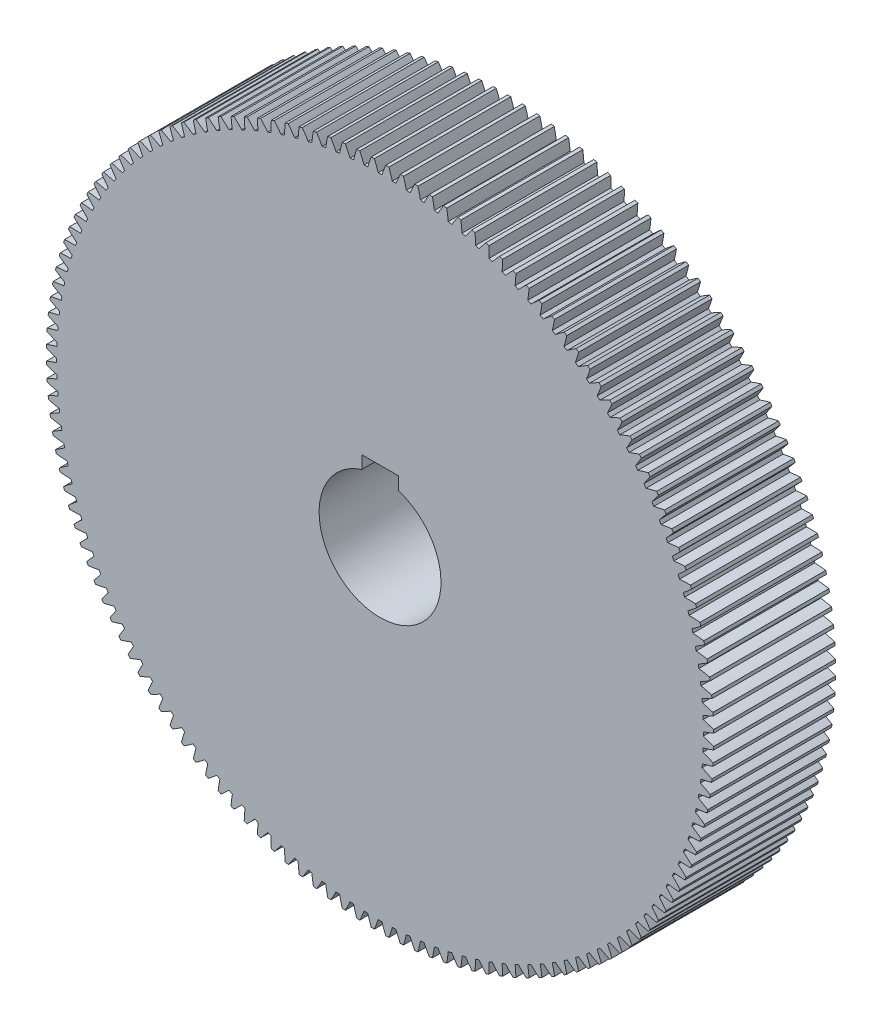
SolidWorks part; units mm, degrees
ref_plane "前视基准面" through (0, 0, 0) normal (0, 0, 1) x (1, 0, 0)
ref_plane "上视基准面" through (0, 0, 0) normal (0, 1, 0) x (1, 0, 0)
ref_plane "右视基准面" through (0, 0, 0) normal (1, 0, 0) x (0, 0, -1)
sketch "Model" plane through (0, 0, 0) normal (0, 0, 1) x (1, 0, 0)
  line L0 (6, 19.0788) -> (6, 23.3)
  line L1 (-6, 23.3) -> (-6, 19.0788)
  line L2 (6, 23.3) -> (-6, 23.3)
  arc A0 (-109.484, 1.8733) -> (-106.1223, 0.6043) centre (-92.5599, 41.6202) ccw
  arc A1 (-106.1223, 0.6043) -> (-106.1223, -0.6043) centre (0, 0) ccw
  arc A2 (-106.1223, -0.6043) -> (-109.484, -1.8733) centre (-92.5599, -41.6202) ccw
  arc A3 (-109.484, -1.8733) -> (-109.4615, -2.9041) centre (0, 0) ccw
  arc A4 (-109.4615, -2.9041) -> (-106.0476, -4.0252) centre (-94.2872, 37.5432) ccw
  arc A5 (-106.0476, -4.0252) -> (-105.9949, -5.2328) centre (0, 0) ccw
  arc A6 (-105.9949, -5.2328) -> (-109.2981, -6.6472) centre (-90.6563, -45.618) ccw
  arc A7 (-109.2981, -6.6472) -> (-109.2306, -7.676) centre (0, 0) ccw
  arc A8 (-109.2306, -7.676) -> (-105.7711, -8.6471) centre (-95.8351, 33.3947) ccw
  arc A9 (-105.7711, -8.6471) -> (-105.6658, -9.8512) centre (0, 0) ccw
  arc A10 (-105.6658, -9.8512) -> (-108.9041, -11.4084) centre (-88.5802, -49.529) ccw
  arc A11 (-108.9041, -11.4084) -> (-108.7918, -12.4332) centre (0, 0) ccw
  arc A12 (-108.7918, -12.4332) -> (-105.2933, -13.2526) centre (-97.2005, 29.1827) ccw
  arc A13 (-105.2933, -13.2526) -> (-105.1355, -14.4509) centre (0, 0) ccw
  arc A14 (-105.1355, -14.4509) -> (-108.3028, -16.1478) centre (-86.3355, -53.3456) ccw
  arc A15 (-108.3028, -16.1478) -> (-108.146, -17.1668) centre (0, 0) ccw
  arc A16 (-108.146, -17.1668) -> (-104.615, -17.8328) centre (-98.3809, 24.9151) ccw
  arc A17 (-104.615, -17.8328) -> (-104.4051, -19.0231) centre (0, 0) ccw
  arc A18 (-104.4051, -19.0231) -> (-107.4954, -20.8566) centre (-83.9264, -57.0608) ccw
  arc A19 (-107.4954, -20.8566) -> (-107.2942, -21.8677) centre (0, 0) ccw
  arc A20 (-107.2942, -21.8677) -> (-103.7376, -22.379) centre (-99.3741, 20.6) ccw
  arc A21 (-103.7376, -22.379) -> (-103.476, -23.5591) centre (0, 0) ccw
  arc A22 (-103.476, -23.5591) -> (-106.4833, -25.5256) centre (-81.3576, -60.6673) ccw
  arc A23 (-106.4833, -25.5256) -> (-106.2383, -26.527) centre (0, 0) ccw
  arc A24 (-106.2383, -26.527) -> (-102.6627, -26.8827) centre (-100.1781, 16.2458) ccw
  arc A25 (-102.6627, -26.8827) -> (-102.3498, -28.0502) centre (0, 0) ccw
  arc A26 (-102.3498, -28.0502) -> (-105.2685, -30.146) centre (-78.6339, -64.1583) ccw
  arc A27 (-105.2685, -30.146) -> (-104.98, -31.1358) centre (0, 0) ccw
  arc A28 (-104.98, -31.1358) -> (-101.3923, -31.3352) centre (-100.7914, 11.8606) ccw
  arc A29 (-101.3923, -31.3352) -> (-101.0289, -32.488) centre (0, 0) ccw
  arc A30 (-101.0289, -32.488) -> (-103.8534, -34.7091) centre (-75.7605, -67.5272) ccw
  arc A31 (-103.8534, -34.7091) -> (-103.522, -35.6854) centre (0, 0) ccw
  arc A32 (-103.522, -35.6854) -> (-99.929, -35.7281) centre (-101.2128, 7.4529) ccw
  arc A33 (-99.929, -35.7281) -> (-99.5156, -36.8639) centre (0, 0) ccw
  arc A34 (-99.5156, -36.8639) -> (-102.2406, -39.2061) centre (-72.7429, -70.7675) ccw
  arc A35 (-102.2406, -39.2061) -> (-101.8669, -40.167) centre (0, 0) ccw
  arc A36 (-101.8669, -40.167) -> (-98.2755, -40.0529) centre (-101.4415, 3.0309) ccw
  arc A37 (-98.2755, -40.0529) -> (-97.8129, -41.1696) centre (0, 0) ccw
  arc A38 (-97.8129, -41.1696) -> (-100.4331, -43.6284) centre (-69.5868, -73.8732) ccw
  arc A39 (-100.4331, -43.6284) -> (-100.0179, -44.5721) centre (0, 0) ccw
  arc A40 (-100.0179, -44.5721) -> (-96.4349, -44.3015) centre (-101.4772, -1.3968) ccw
  arc A41 (-96.4349, -44.3015) -> (-95.924, -45.3969) centre (0, 0) ccw
  arc A42 (-95.924, -45.3969) -> (-98.4345, -47.9677) centre (-66.2983, -76.8382) ccw
  arc A43 (-98.4345, -47.9677) -> (-97.9785, -48.8924) centre (0, 0) ccw
  arc A44 (-97.9785, -48.8924) -> (-94.4107, -48.4658) centre (-101.3197, -5.8218) ccw
  arc A45 (-94.4107, -48.4658) -> (-93.8526, -49.5379) centre (0, 0) ccw
  arc A46 (-93.8526, -49.5379) -> (-96.2485, -52.2157) centre (-62.8835, -79.657) ccw
  arc A47 (-96.2485, -52.2157) -> (-95.7526, -53.1196) centre (0, 0) ccw
  arc A48 (-95.7526, -53.1196) -> (-92.2068, -52.5378) centre (-100.9693, -10.2358) ccw
  arc A49 (-92.2068, -52.5378) -> (-91.6024, -53.5845) centre (0, 0) ccw
  arc A50 (-91.6024, -53.5845) -> (-93.8792, -56.3643) centre (-59.3491, -82.3241) ccw
  arc A51 (-93.8792, -56.3643) -> (-93.3444, -57.2457) centre (0, 0) ccw
  arc A52 (-93.3444, -57.2457) -> (-89.8273, -56.5098) centre (-100.4267, -14.6303) ccw
  arc A53 (-89.8273, -56.5098) -> (-89.1779, -57.5292) centre (0, 0) ccw
  arc A54 (-89.1779, -57.5292) -> (-91.3313, -60.4056) centre (-55.7017, -84.8345) ccw
  arc A55 (-91.3313, -60.4056) -> (-90.7585, -61.2629) centre (0, 0) ccw
  arc A56 (-90.7585, -61.2629) -> (-87.2769, -60.3742) centre (-99.693, -18.9969) ccw
  arc A57 (-87.2769, -60.3742) -> (-86.5836, -61.3643) centre (0, 0) ccw
  arc A58 (-86.5836, -61.3643) -> (-88.6095, -64.332) centre (-51.9482, -87.1834) ccw
  arc A59 (-88.6095, -64.332) -> (-87.9999, -65.1634) centre (0, 0) ccw
  arc A60 (-87.9999, -65.1634) -> (-84.5604, -64.1237) centre (-98.7695, -23.3273) ccw
  arc A61 (-84.5604, -64.1237) -> (-83.8246, -65.0826) centre (0, 0) ccw
  arc A62 (-83.8246, -65.0826) -> (-85.7191, -68.1358) centre (-48.0959, -89.3664) ccw
  arc A63 (-85.7191, -68.1358) -> (-85.0737, -68.9399) centre (0, 0) ccw
  arc A64 (-85.0737, -68.9399) -> (-81.6829, -67.7511) centre (-97.6579, -27.6134) ccw
  arc A65 (-81.6829, -67.7511) -> (-80.9059, -68.677) centre (0, 0) ccw
  arc A66 (-80.9059, -68.677) -> (-82.6654, -71.81) centre (-44.152, -91.3793) ccw
  arc A67 (-82.6654, -71.81) -> (-81.9857, -72.5851) centre (0, 0) ccw
  arc A68 (-81.9857, -72.5851) -> (-78.6498, -71.2496) centre (-96.3605, -31.8469) ccw
  arc A69 (-78.6498, -71.2496) -> (-77.8333, -72.1407) centre (0, 0) ccw
  arc A70 (-77.8333, -72.1407) -> (-79.4544, -75.3475) centre (-40.1241, -93.2182) ccw
  arc A71 (-79.4544, -75.3475) -> (-78.7415, -76.0922) centre (0, 0) ccw
  arc A72 (-78.7415, -76.0922) -> (-75.4671, -74.6124) centre (-94.8796, -36.0198) ccw
  arc A73 (-75.4671, -74.6124) -> (-74.6124, -75.4671) centre (0, 0) ccw
  arc A74 (-74.6124, -75.4671) -> (-76.0922, -78.7415) centre (-36.0198, -94.8796) ccw
  arc A75 (-76.0922, -78.7415) -> (-75.3475, -79.4544) centre (0, 0) ccw
  arc A76 (-75.3475, -79.4544) -> (-72.1407, -77.8333) centre (-93.2182, -40.1241) ccw
  arc A77 (-72.1407, -77.8333) -> (-71.2496, -78.6498) centre (0, 0) ccw
  arc A78 (-71.2496, -78.6498) -> (-72.5851, -81.9857) centre (-31.8469, -96.3605) ccw
  arc A79 (-72.5851, -81.9857) -> (-71.81, -82.6654) centre (0, 0) ccw
  arc A80 (-71.81, -82.6654) -> (-68.677, -80.9059) centre (-91.3793, -44.152) ccw
  arc A81 (-68.677, -80.9059) -> (-67.7511, -81.6829) centre (0, 0) ccw
  arc A82 (-67.7511, -81.6829) -> (-68.9399, -85.0737) centre (-27.6134, -97.6579) ccw
  arc A83 (-68.9399, -85.0737) -> (-68.1358, -85.7191) centre (0, 0) ccw
  arc A84 (-68.1358, -85.7191) -> (-65.0826, -83.8246) centre (-89.3664, -48.0959) ccw
  arc A85 (-65.0826, -83.8246) -> (-64.1237, -84.5604) centre (0, 0) ccw
  arc A86 (-64.1237, -84.5604) -> (-65.1634, -87.9999) centre (-23.3273, -98.7695) ccw
  arc A87 (-65.1634, -87.9999) -> (-64.332, -88.6095) centre (0, 0) ccw
  arc A88 (-64.332, -88.6095) -> (-61.3643, -86.5836) centre (-87.1834, -51.9482) ccw
  arc A89 (-61.3643, -86.5836) -> (-60.3742, -87.2769) centre (0, 0) ccw
  arc A90 (-60.3742, -87.2769) -> (-61.2629, -90.7585) centre (-18.9969, -99.693) ccw
  arc A91 (-61.2629, -90.7585) -> (-60.4056, -91.3313) centre (0, 0) ccw
  arc A92 (-60.4056, -91.3313) -> (-57.5292, -89.1779) centre (-84.8345, -55.7017) ccw
  arc A93 (-57.5292, -89.1779) -> (-56.5098, -89.8273) centre (0, 0) ccw
  arc A94 (-56.5098, -89.8273) -> (-57.2457, -93.3444) centre (-14.6303, -100.4267) ccw
  arc A95 (-57.2457, -93.3444) -> (-56.3643, -93.8792) centre (0, 0) ccw
  arc A96 (-56.3643, -93.8792) -> (-53.5845, -91.6024) centre (-82.3241, -59.3491) ccw
  arc A97 (-53.5845, -91.6024) -> (-52.5378, -92.2068) centre (0, 0) ccw
  arc A98 (-52.5378, -92.2068) -> (-53.1196, -95.7526) centre (-10.2358, -100.9693) ccw
  arc A99 (-53.1196, -95.7526) -> (-52.2157, -96.2485) centre (0, 0) ccw
  arc A100 (-52.2157, -96.2485) -> (-49.5379, -93.8526) centre (-79.657, -62.8835) ccw
  arc A101 (-49.5379, -93.8526) -> (-48.4658, -94.4107) centre (0, 0) ccw
  arc A102 (-48.4658, -94.4107) -> (-48.8924, -97.9785) centre (-5.8218, -101.3197) ccw
  arc A103 (-48.8924, -97.9785) -> (-47.9677, -98.4345) centre (0, 0) ccw
  arc A104 (-47.9677, -98.4345) -> (-45.3969, -95.924) centre (-76.8382, -66.2983) ccw
  arc A105 (-45.3969, -95.924) -> (-44.3015, -96.4349) centre (0, 0) ccw
  arc A106 (-44.3015, -96.4349) -> (-44.5721, -100.0179) centre (-1.3968, -101.4772) ccw
  arc A107 (-44.5721, -100.0179) -> (-43.6284, -100.4331) centre (0, 0) ccw
  arc A108 (-43.6284, -100.4331) -> (-41.1696, -97.8129) centre (-73.8732, -69.5868) ccw
  arc A109 (-41.1696, -97.8129) -> (-40.0529, -98.2755) centre (0, 0) ccw
  arc A110 (-40.0529, -98.2755) -> (-40.167, -101.8669) centre (3.0309, -101.4415) ccw
  arc A111 (-40.167, -101.8669) -> (-39.2061, -102.2406) centre (0, 0) ccw
  arc A112 (-39.2061, -102.2406) -> (-36.8639, -99.5156) centre (-70.7675, -72.7429) ccw
  arc A113 (-36.8639, -99.5156) -> (-35.7281, -99.929) centre (0, 0) ccw
  arc A114 (-35.7281, -99.929) -> (-35.6854, -103.522) centre (7.4529, -101.2128) ccw
  arc A115 (-35.6854, -103.522) -> (-34.7091, -103.8534) centre (0, 0) ccw
  arc A116 (-34.7091, -103.8534) -> (-32.488, -101.0289) centre (-67.5272, -75.7605) ccw
  arc A117 (-32.488, -101.0289) -> (-31.3352, -101.3923) centre (0, 0) ccw
  arc A118 (-31.3352, -101.3923) -> (-31.1358, -104.98) centre (11.8606, -100.7914) ccw
  arc A119 (-31.1358, -104.98) -> (-30.146, -105.2685) centre (0, 0) ccw
  arc A120 (-30.146, -105.2685) -> (-28.0502, -102.3498) centre (-64.1583, -78.6339) ccw
  arc A121 (-28.0502, -102.3498) -> (-26.8827, -102.6627) centre (0, 0) ccw
  arc A122 (-26.8827, -102.6627) -> (-26.527, -106.2383) centre (16.2458, -100.1781) ccw
  arc A123 (-26.527, -106.2383) -> (-25.5256, -106.4833) centre (0, 0) ccw
  arc A124 (-25.5256, -106.4833) -> (-23.5591, -103.476) centre (-60.6673, -81.3576) ccw
  arc A125 (-23.5591, -103.476) -> (-22.379, -103.7376) centre (0, 0) ccw
  arc A126 (-22.379, -103.7376) -> (-21.8677, -107.2942) centre (20.6, -99.3741) ccw
  arc A127 (-21.8677, -107.2942) -> (-20.8566, -107.4954) centre (0, 0) ccw
  arc A128 (-20.8566, -107.4954) -> (-19.0231, -104.4051) centre (-57.0608, -83.9264) ccw
  arc A129 (-19.0231, -104.4051) -> (-17.8328, -104.615) centre (0, 0) ccw
  arc A130 (-17.8328, -104.615) -> (-17.1668, -108.146) centre (24.9151, -98.3809) ccw
  arc A131 (-17.1668, -108.146) -> (-16.1478, -108.3028) centre (0, 0) ccw
  arc A132 (-16.1478, -108.3028) -> (-14.4509, -105.1355) centre (-53.3456, -86.3355) ccw
  arc A133 (-14.4509, -105.1355) -> (-13.2526, -105.2933) centre (0, 0) ccw
  arc A134 (-13.2526, -105.2933) -> (-12.4332, -108.7918) centre (29.1827, -97.2005) ccw
  arc A135 (-12.4332, -108.7918) -> (-11.4084, -108.9041) centre (0, 0) ccw
  arc A136 (-11.4084, -108.9041) -> (-9.8512, -105.6658) centre (-49.529, -88.5802) ccw
  arc A137 (-9.8512, -105.6658) -> (-8.6471, -105.7711) centre (0, 0) ccw
  arc A138 (-8.6471, -105.7711) -> (-7.676, -109.2306) centre (33.3947, -95.8351) ccw
  arc A139 (-7.676, -109.2306) -> (-6.6472, -109.2981) centre (0, 0) ccw
  arc A140 (-6.6472, -109.2981) -> (-5.2328, -105.9949) centre (-45.618, -90.6563) ccw
  arc A141 (-5.2328, -105.9949) -> (-4.0252, -106.0476) centre (0, 0) ccw
  arc A142 (-4.0252, -106.0476) -> (-2.9041, -109.4615) centre (37.5432, -94.2872) ccw
  arc A143 (-2.9041, -109.4615) -> (-1.8733, -109.484) centre (0, 0) ccw
  arc A144 (-1.8733, -109.484) -> (-0.6043, -106.1223) centre (-41.6202, -92.5599) ccw
  arc A145 (-0.6043, -106.1223) -> (0.6043, -106.1223) centre (0, 0) ccw
  arc A146 (0.6043, -106.1223) -> (1.8733, -109.484) centre (41.6202, -92.5599) ccw
  arc A147 (1.8733, -109.484) -> (2.9041, -109.4615) centre (0, 0) ccw
  arc A148 (2.9041, -109.4615) -> (4.0252, -106.0476) centre (-37.5432, -94.2872) ccw
  arc A149 (4.0252, -106.0476) -> (5.2328, -105.9949) centre (0, 0) ccw
  arc A150 (5.2328, -105.9949) -> (6.6472, -109.2981) centre (45.618, -90.6563) ccw
  arc A151 (6.6472, -109.2981) -> (7.676, -109.2306) centre (0, 0) ccw
  arc A152 (7.676, -109.2306) -> (8.6471, -105.7711) centre (-33.3947, -95.8351) ccw
  arc A153 (8.6471, -105.7711) -> (9.8512, -105.6658) centre (0, 0) ccw
  arc A154 (9.8512, -105.6658) -> (11.4084, -108.9041) centre (49.529, -88.5802) ccw
  arc A155 (11.4084, -108.9041) -> (12.4332, -108.7918) centre (0, 0) ccw
  arc A156 (12.4332, -108.7918) -> (13.2526, -105.2933) centre (-29.1827, -97.2005) ccw
  arc A157 (13.2526, -105.2933) -> (14.4509, -105.1355) centre (0, 0) ccw
  arc A158 (14.4509, -105.1355) -> (16.1478, -108.3028) centre (53.3456, -86.3355) ccw
  arc A159 (16.1478, -108.3028) -> (17.1668, -108.146) centre (0, 0) ccw
  arc A160 (17.1668, -108.146) -> (17.8328, -104.615) centre (-24.9151, -98.3809) ccw
  arc A161 (17.8328, -104.615) -> (19.0231, -104.4051) centre (0, 0) ccw
  arc A162 (19.0231, -104.4051) -> (20.8566, -107.4954) centre (57.0608, -83.9264) ccw
  arc A163 (20.8566, -107.4954) -> (21.8677, -107.2942) centre (0, 0) ccw
  arc A164 (21.8677, -107.2942) -> (22.379, -103.7376) centre (-20.6, -99.3741) ccw
  arc A165 (22.379, -103.7376) -> (23.5591, -103.476) centre (0, 0) ccw
  arc A166 (23.5591, -103.476) -> (25.5256, -106.4833) centre (60.6673, -81.3576) ccw
  arc A167 (25.5256, -106.4833) -> (26.527, -106.2383) centre (0, 0) ccw
  arc A168 (26.527, -106.2383) -> (26.8827, -102.6627) centre (-16.2458, -100.1781) ccw
  arc A169 (26.8827, -102.6627) -> (28.0502, -102.3498) centre (0, 0) ccw
  arc A170 (28.0502, -102.3498) -> (30.146, -105.2685) centre (64.1583, -78.6339) ccw
  arc A171 (30.146, -105.2685) -> (31.1358, -104.98) centre (0, 0) ccw
  arc A172 (31.1358, -104.98) -> (31.3352, -101.3923) centre (-11.8606, -100.7914) ccw
  arc A173 (31.3352, -101.3923) -> (32.488, -101.0289) centre (0, 0) ccw
  arc A174 (32.488, -101.0289) -> (34.7091, -103.8534) centre (67.5272, -75.7605) ccw
  arc A175 (34.7091, -103.8534) -> (35.6854, -103.522) centre (0, 0) ccw
  arc A176 (35.6854, -103.522) -> (35.7281, -99.929) centre (-7.4529, -101.2128) ccw
  arc A177 (35.7281, -99.929) -> (36.8639, -99.5156) centre (0, 0) ccw
  arc A178 (36.8639, -99.5156) -> (39.2061, -102.2406) centre (70.7675, -72.7429) ccw
  arc A179 (39.2061, -102.2406) -> (40.167, -101.8669) centre (0, 0) ccw
  arc A180 (40.167, -101.8669) -> (40.0529, -98.2755) centre (-3.0309, -101.4415) ccw
  arc A181 (40.0529, -98.2755) -> (41.1696, -97.8129) centre (0, 0) ccw
  arc A182 (41.1696, -97.8129) -> (43.6284, -100.4331) centre (73.8732, -69.5868) ccw
  arc A183 (43.6284, -100.4331) -> (44.5721, -100.0179) centre (0, 0) ccw
  arc A184 (44.5721, -100.0179) -> (44.3015, -96.4349) centre (1.3968, -101.4772) ccw
  arc A185 (44.3015, -96.4349) -> (45.3969, -95.924) centre (0, 0) ccw
  arc A186 (45.3969, -95.924) -> (47.9677, -98.4345) centre (76.8382, -66.2983) ccw
  arc A187 (47.9677, -98.4345) -> (48.8924, -97.9785) centre (0, 0) ccw
  arc A188 (48.8924, -97.9785) -> (48.4658, -94.4107) centre (5.8218, -101.3197) ccw
  arc A189 (48.4658, -94.4107) -> (49.5379, -93.8526) centre (0, 0) ccw
  arc A190 (49.5379, -93.8526) -> (52.2157, -96.2485) centre (79.657, -62.8835) ccw
  arc A191 (52.2157, -96.2485) -> (53.1196, -95.7526) centre (0, 0) ccw
  arc A192 (53.1196, -95.7526) -> (52.5378, -92.2068) centre (10.2358, -100.9693) ccw
  arc A193 (52.5378, -92.2068) -> (53.5845, -91.6024) centre (0, 0) ccw
  arc A194 (53.5845, -91.6024) -> (56.3643, -93.8792) centre (82.3241, -59.3491) ccw
  arc A195 (56.3643, -93.8792) -> (57.2457, -93.3444) centre (0, 0) ccw
  arc A196 (57.2457, -93.3444) -> (56.5098, -89.8273) centre (14.6303, -100.4267) ccw
  arc A197 (56.5098, -89.8273) -> (57.5292, -89.1779) centre (0, 0) ccw
  arc A198 (57.5292, -89.1779) -> (60.4056, -91.3313) centre (84.8345, -55.7017) ccw
  arc A199 (60.4056, -91.3313) -> (61.2629, -90.7585) centre (0, 0) ccw
  arc A200 (61.2629, -90.7585) -> (60.3742, -87.2769) centre (18.9969, -99.693) ccw
  arc A201 (60.3742, -87.2769) -> (61.3643, -86.5836) centre (0, 0) ccw
  arc A202 (61.3643, -86.5836) -> (64.332, -88.6095) centre (87.1834, -51.9482) ccw
  arc A203 (64.332, -88.6095) -> (65.1634, -87.9999) centre (0, 0) ccw
  arc A204 (65.1634, -87.9999) -> (64.1237, -84.5604) centre (23.3273, -98.7695) ccw
  arc A205 (64.1237, -84.5604) -> (65.0826, -83.8246) centre (0, 0) ccw
  arc A206 (65.0826, -83.8246) -> (68.1358, -85.7191) centre (89.3664, -48.0959) ccw
  arc A207 (68.1358, -85.7191) -> (68.9399, -85.0737) centre (0, 0) ccw
  arc A208 (68.9399, -85.0737) -> (67.7511, -81.6829) centre (27.6134, -97.6579) ccw
  arc A209 (67.7511, -81.6829) -> (68.677, -80.9059) centre (0, 0) ccw
  arc A210 (68.677, -80.9059) -> (71.81, -82.6654) centre (91.3793, -44.152) ccw
  arc A211 (71.81, -82.6654) -> (72.5851, -81.9857) centre (0, 0) ccw
  arc A212 (72.5851, -81.9857) -> (71.2496, -78.6498) centre (31.8469, -96.3605) ccw
  arc A213 (71.2496, -78.6498) -> (72.1407, -77.8333) centre (0, 0) ccw
  arc A214 (72.1407, -77.8333) -> (75.3475, -79.4544) centre (93.2182, -40.1241) ccw
  arc A215 (75.3475, -79.4544) -> (76.0922, -78.7415) centre (0, 0) ccw
  arc A216 (76.0922, -78.7415) -> (74.6124, -75.4671) centre (36.0198, -94.8796) ccw
  arc A217 (74.6124, -75.4671) -> (75.4671, -74.6124) centre (0, 0) ccw
  arc A218 (75.4671, -74.6124) -> (78.7415, -76.0922) centre (94.8796, -36.0198) ccw
  arc A219 (78.7415, -76.0922) -> (79.4544, -75.3475) centre (0, 0) ccw
  arc A220 (79.4544, -75.3475) -> (77.8333, -72.1407) centre (40.1241, -93.2182) ccw
  arc A221 (77.8333, -72.1407) -> (78.6498, -71.2496) centre (0, 0) ccw
  arc A222 (78.6498, -71.2496) -> (81.9857, -72.5851) centre (96.3605, -31.8469) ccw
  arc A223 (81.9857, -72.5851) -> (82.6654, -71.81) centre (0, 0) ccw
  arc A224 (82.6654, -71.81) -> (80.9059, -68.677) centre (44.152, -91.3793) ccw
  arc A225 (80.9059, -68.677) -> (81.6829, -67.7511) centre (0, 0) ccw
  arc A226 (81.6829, -67.7511) -> (85.0737, -68.9399) centre (97.6579, -27.6134) ccw
  arc A227 (85.0737, -68.9399) -> (85.7191, -68.1358) centre (0, 0) ccw
  arc A228 (85.7191, -68.1358) -> (83.8246, -65.0826) centre (48.0959, -89.3664) ccw
  arc A229 (83.8246, -65.0826) -> (84.5604, -64.1237) centre (0, 0) ccw
  arc A230 (84.5604, -64.1237) -> (87.9999, -65.1634) centre (98.7695, -23.3273) ccw
  arc A231 (87.9999, -65.1634) -> (88.6095, -64.332) centre (0, 0) ccw
  arc A232 (88.6095, -64.332) -> (86.5836, -61.3643) centre (51.9482, -87.1834) ccw
  arc A233 (86.5836, -61.3643) -> (87.2769, -60.3742) centre (0, 0) ccw
  arc A234 (87.2769, -60.3742) -> (90.7585, -61.2629) centre (99.693, -18.9969) ccw
  arc A235 (90.7585, -61.2629) -> (91.3313, -60.4056) centre (0, 0) ccw
  arc A236 (91.3313, -60.4056) -> (89.1779, -57.5292) centre (55.7017, -84.8345) ccw
  arc A237 (89.1779, -57.5292) -> (89.8273, -56.5098) centre (0, 0) ccw
  arc A238 (89.8273, -56.5098) -> (93.3444, -57.2457) centre (100.4267, -14.6303) ccw
  arc A239 (93.3444, -57.2457) -> (93.8792, -56.3643) centre (0, 0) ccw
  arc A240 (93.8792, -56.3643) -> (91.6024, -53.5845) centre (59.3491, -82.3241) ccw
  arc A241 (91.6024, -53.5845) -> (92.2068, -52.5378) centre (0, 0) ccw
  arc A242 (92.2068, -52.5378) -> (95.7526, -53.1196) centre (100.9693, -10.2358) ccw
  arc A243 (95.7526, -53.1196) -> (96.2485, -52.2157) centre (0, 0) ccw
  arc A244 (96.2485, -52.2157) -> (93.8526, -49.5379) centre (62.8835, -79.657) ccw
  arc A245 (93.8526, -49.5379) -> (94.4107, -48.4658) centre (0, 0) ccw
  arc A246 (94.4107, -48.4658) -> (97.9785, -48.8924) centre (101.3197, -5.8218) ccw
  arc A247 (97.9785, -48.8924) -> (98.4345, -47.9677) centre (0, 0) ccw
  arc A248 (98.4345, -47.9677) -> (95.924, -45.3969) centre (66.2983, -76.8382) ccw
  arc A249 (95.924, -45.3969) -> (96.4349, -44.3015) centre (0, 0) ccw
  arc A250 (96.4349, -44.3015) -> (100.0179, -44.5721) centre (101.4772, -1.3968) ccw
  arc A251 (100.0179, -44.5721) -> (100.4331, -43.6284) centre (0, 0) ccw
  arc A252 (100.4331, -43.6284) -> (97.8129, -41.1696) centre (69.5868, -73.8732) ccw
  arc A253 (97.8129, -41.1696) -> (98.2755, -40.0529) centre (0, 0) ccw
  arc A254 (98.2755, -40.0529) -> (101.8669, -40.167) centre (101.4415, 3.0309) ccw
  arc A255 (101.8669, -40.167) -> (102.2406, -39.2061) centre (0, 0) ccw
  arc A256 (102.2406, -39.2061) -> (99.5156, -36.8639) centre (72.7429, -70.7675) ccw
  arc A257 (99.5156, -36.8639) -> (99.929, -35.7281) centre (0, 0) ccw
  arc A258 (99.929, -35.7281) -> (103.522, -35.6854) centre (101.2128, 7.4529) ccw
  arc A259 (103.522, -35.6854) -> (103.8534, -34.7091) centre (0, 0) ccw
  arc A260 (103.8534, -34.7091) -> (101.0289, -32.488) centre (75.7605, -67.5272) ccw
  arc A261 (101.0289, -32.488) -> (101.3923, -31.3352) centre (0, 0) ccw
  arc A262 (101.3923, -31.3352) -> (104.98, -31.1358) centre (100.7914, 11.8606) ccw
  arc A263 (104.98, -31.1358) -> (105.2685, -30.146) centre (0, 0) ccw
  arc A264 (105.2685, -30.146) -> (102.3498, -28.0502) centre (78.6339, -64.1583) ccw
  arc A265 (102.3498, -28.0502) -> (102.6627, -26.8827) centre (0, 0) ccw
  arc A266 (102.6627, -26.8827) -> (106.2383, -26.527) centre (100.1781, 16.2458) ccw
  arc A267 (106.2383, -26.527) -> (106.4833, -25.5256) centre (0, 0) ccw
  arc A268 (106.4833, -25.5256) -> (103.476, -23.5591) centre (81.3576, -60.6673) ccw
  arc A269 (103.476, -23.5591) -> (103.7376, -22.379) centre (0, 0) ccw
  arc A270 (103.7376, -22.379) -> (107.2942, -21.8677) centre (99.3741, 20.6) ccw
  arc A271 (107.2942, -21.8677) -> (107.4954, -20.8566) centre (0, 0) ccw
  arc A272 (107.4954, -20.8566) -> (104.4051, -19.0231) centre (83.9264, -57.0608) ccw
  arc A273 (104.4051, -19.0231) -> (104.615, -17.8328) centre (0, 0) ccw
  arc A274 (104.615, -17.8328) -> (108.146, -17.1668) centre (98.3809, 24.9151) ccw
  arc A275 (108.146, -17.1668) -> (108.3028, -16.1478) centre (0, 0) ccw
  arc A276 (108.3028, -16.1478) -> (105.1355, -14.4509) centre (86.3355, -53.3456) ccw
  arc A277 (105.1355, -14.4509) -> (105.2933, -13.2526) centre (0, 0) ccw
  arc A278 (105.2933, -13.2526) -> (108.7918, -12.4332) centre (97.2005, 29.1827) ccw
  arc A279 (108.7918, -12.4332) -> (108.9041, -11.4084) centre (0, 0) ccw
  arc A280 (108.9041, -11.4084) -> (105.6658, -9.8512) centre (88.5802, -49.529) ccw
  arc A281 (105.6658, -9.8512) -> (105.7711, -8.6471) centre (0, 0) ccw
  arc A282 (105.7711, -8.6471) -> (109.2306, -7.676) centre (95.8351, 33.3947) ccw
  arc A283 (109.2306, -7.676) -> (109.2981, -6.6472) centre (0, 0) ccw
  arc A284 (109.2981, -6.6472) -> (105.9949, -5.2328) centre (90.6563, -45.618) ccw
  arc A285 (105.9949, -5.2328) -> (106.0476, -4.0252) centre (0, 0) ccw
  arc A286 (106.0476, -4.0252) -> (109.4615, -2.9041) centre (94.2872, 37.5432) ccw
  arc A287 (109.4615, -2.9041) -> (109.484, -1.8733) centre (0, 0) ccw
  arc A288 (109.484, -1.8733) -> (106.1223, -0.6043) centre (92.5599, -41.6202) ccw
  arc A289 (106.1223, -0.6043) -> (106.1223, 0.6043) centre (0, 0) ccw
  arc A290 (106.1223, 0.6043) -> (109.484, 1.8733) centre (92.5599, 41.6202) ccw
  arc A291 (109.484, 1.8733) -> (109.4615, 2.9041) centre (0, 0) ccw
  arc A292 (109.4615, 2.9041) -> (106.0476, 4.0252) centre (94.2872, -37.5432) ccw
  arc A293 (106.0476, 4.0252) -> (105.9949, 5.2328) centre (0, 0) ccw
  arc A294 (105.9949, 5.2328) -> (109.2981, 6.6472) centre (90.6563, 45.618) ccw
  arc A295 (109.2981, 6.6472) -> (109.2306, 7.676) centre (0, 0) ccw
  arc A296 (109.2306, 7.676) -> (105.7711, 8.6471) centre (95.8351, -33.3947) ccw
  arc A297 (105.7711, 8.6471) -> (105.6658, 9.8512) centre (0, 0) ccw
  arc A298 (105.6658, 9.8512) -> (108.9041, 11.4084) centre (88.5802, 49.529) ccw
  arc A299 (108.9041, 11.4084) -> (108.7918, 12.4332) centre (0, 0) ccw
  arc A300 (108.7918, 12.4332) -> (105.2933, 13.2526) centre (97.2005, -29.1827) ccw
  arc A301 (105.2933, 13.2526) -> (105.1355, 14.4509) centre (0, 0) ccw
  arc A302 (105.1355, 14.4509) -> (108.3028, 16.1478) centre (86.3355, 53.3456) ccw
  arc A303 (108.3028, 16.1478) -> (108.146, 17.1668) centre (0, 0) ccw
  arc A304 (108.146, 17.1668) -> (104.615, 17.8328) centre (98.3809, -24.9151) ccw
  arc A305 (104.615, 17.8328) -> (104.4051, 19.0231) centre (0, 0) ccw
  arc A306 (104.4051, 19.0231) -> (107.4954, 20.8566) centre (83.9264, 57.0608) ccw
  arc A307 (107.4954, 20.8566) -> (107.2942, 21.8677) centre (0, 0) ccw
  arc A308 (107.2942, 21.8677) -> (103.7376, 22.379) centre (99.3741, -20.6) ccw
  arc A309 (103.7376, 22.379) -> (103.476, 23.5591) centre (0, 0) ccw
  arc A310 (103.476, 23.5591) -> (106.4833, 25.5256) centre (81.3576, 60.6673) ccw
  arc A311 (106.4833, 25.5256) -> (106.2383, 26.527) centre (0, 0) ccw
  arc A312 (106.2383, 26.527) -> (102.6627, 26.8827) centre (100.1781, -16.2458) ccw
  arc A313 (102.6627, 26.8827) -> (102.3498, 28.0502) centre (0, 0) ccw
  arc A314 (102.3498, 28.0502) -> (105.2685, 30.146) centre (78.6339, 64.1583) ccw
  arc A315 (105.2685, 30.146) -> (104.98, 31.1358) centre (0, 0) ccw
  arc A316 (104.98, 31.1358) -> (101.3923, 31.3352) centre (100.7914, -11.8606) ccw
  arc A317 (101.3923, 31.3352) -> (101.0289, 32.488) centre (0, 0) ccw
  arc A318 (101.0289, 32.488) -> (103.8534, 34.7091) centre (75.7605, 67.5272) ccw
  arc A319 (103.8534, 34.7091) -> (103.522, 35.6854) centre (0, 0) ccw
  arc A320 (103.522, 35.6854) -> (99.929, 35.7281) centre (101.2128, -7.4529) ccw
  arc A321 (99.929, 35.7281) -> (99.5156, 36.8639) centre (0, 0) ccw
  arc A322 (99.5156, 36.8639) -> (102.2406, 39.2061) centre (72.7429, 70.7675) ccw
  arc A323 (102.2406, 39.2061) -> (101.8669, 40.167) centre (0, 0) ccw
  arc A324 (101.8669, 40.167) -> (98.2755, 40.0529) centre (101.4415, -3.0309) ccw
  arc A325 (98.2755, 40.0529) -> (97.8129, 41.1696) centre (0, 0) ccw
  arc A326 (97.8129, 41.1696) -> (100.4331, 43.6284) centre (69.5868, 73.8732) ccw
  arc A327 (100.4331, 43.6284) -> (100.0179, 44.5721) centre (0, 0) ccw
  arc A328 (100.0179, 44.5721) -> (96.4349, 44.3015) centre (101.4772, 1.3968) ccw
  arc A329 (96.4349, 44.3015) -> (95.924, 45.3969) centre (0, 0) ccw
  arc A330 (95.924, 45.3969) -> (98.4345, 47.9677) centre (66.2983, 76.8382) ccw
  arc A331 (98.4345, 47.9677) -> (97.9785, 48.8924) centre (0, 0) ccw
  arc A332 (97.9785, 48.8924) -> (94.4107, 48.4658) centre (101.3197, 5.8218) ccw
  arc A333 (94.4107, 48.4658) -> (93.8526, 49.5379) centre (0, 0) ccw
  arc A334 (93.8526, 49.5379) -> (96.2485, 52.2157) centre (62.8835, 79.657) ccw
  arc A335 (96.2485, 52.2157) -> (95.7526, 53.1196) centre (0, 0) ccw
  arc A336 (95.7526, 53.1196) -> (92.2068, 52.5378) centre (100.9693, 10.2358) ccw
  arc A337 (92.2068, 52.5378) -> (91.6024, 53.5845) centre (0, 0) ccw
  arc A338 (91.6024, 53.5845) -> (93.8792, 56.3643) centre (59.3491, 82.3241) ccw
  arc A339 (93.8792, 56.3643) -> (93.3444, 57.2457) centre (0, 0) ccw
  arc A340 (93.3444, 57.2457) -> (89.8273, 56.5098) centre (100.4267, 14.6303) ccw
  arc A341 (89.8273, 56.5098) -> (89.1779, 57.5292) centre (0, 0) ccw
  arc A342 (89.1779, 57.5292) -> (91.3313, 60.4056) centre (55.7017, 84.8345) ccw
  arc A343 (91.3313, 60.4056) -> (90.7585, 61.2629) centre (0, 0) ccw
  arc A344 (90.7585, 61.2629) -> (87.2769, 60.3742) centre (99.693, 18.9969) ccw
  arc A345 (87.2769, 60.3742) -> (86.5836, 61.3643) centre (0, 0) ccw
  arc A346 (86.5836, 61.3643) -> (88.6095, 64.332) centre (51.9482, 87.1834) ccw
  arc A347 (88.6095, 64.332) -> (87.9999, 65.1634) centre (0, 0) ccw
  arc A348 (87.9999, 65.1634) -> (84.5604, 64.1237) centre (98.7695, 23.3273) ccw
  arc A349 (84.5604, 64.1237) -> (83.8246, 65.0826) centre (0, 0) ccw
  arc A350 (83.8246, 65.0826) -> (85.7191, 68.1358) centre (48.0959, 89.3664) ccw
  arc A351 (85.7191, 68.1358) -> (85.0737, 68.9399) centre (0, 0) ccw
  arc A352 (85.0737, 68.9399) -> (81.6829, 67.7511) centre (97.6579, 27.6134) ccw
  arc A353 (81.6829, 67.7511) -> (80.9059, 68.677) centre (0, 0) ccw
  arc A354 (80.9059, 68.677) -> (82.6654, 71.81) centre (44.152, 91.3793) ccw
  arc A355 (82.6654, 71.81) -> (81.9857, 72.5851) centre (0, 0) ccw
  arc A356 (81.9857, 72.5851) -> (78.6498, 71.2496) centre (96.3605, 31.8469) ccw
  arc A357 (78.6498, 71.2496) -> (77.8333, 72.1407) centre (0, 0) ccw
  arc A358 (77.8333, 72.1407) -> (79.4544, 75.3475) centre (40.1241, 93.2182) ccw
  arc A359 (79.4544, 75.3475) -> (78.7415, 76.0922) centre (0, 0) ccw
  arc A360 (78.7415, 76.0922) -> (75.4671, 74.6124) centre (94.8796, 36.0198) ccw
  arc A361 (75.4671, 74.6124) -> (74.6124, 75.4671) centre (0, 0) ccw
  arc A362 (74.6124, 75.4671) -> (76.0922, 78.7415) centre (36.0198, 94.8796) ccw
  arc A363 (76.0922, 78.7415) -> (75.3475, 79.4544) centre (0, 0) ccw
  arc A364 (75.3475, 79.4544) -> (72.1407, 77.8333) centre (93.2182, 40.1241) ccw
  arc A365 (72.1407, 77.8333) -> (71.2496, 78.6498) centre (0, 0) ccw
  arc A366 (71.2496, 78.6498) -> (72.5851, 81.9857) centre (31.8469, 96.3605) ccw
  arc A367 (72.5851, 81.9857) -> (71.81, 82.6654) centre (0, 0) ccw
  arc A368 (71.81, 82.6654) -> (68.677, 80.9059) centre (91.3793, 44.152) ccw
  arc A369 (68.677, 80.9059) -> (67.7511, 81.6829) centre (0, 0) ccw
  arc A370 (67.7511, 81.6829) -> (68.9399, 85.0737) centre (27.6134, 97.6579) ccw
  arc A371 (68.9399, 85.0737) -> (68.1358, 85.7191) centre (0, 0) ccw
  arc A372 (68.1358, 85.7191) -> (65.0826, 83.8246) centre (89.3664, 48.0959) ccw
  arc A373 (65.0826, 83.8246) -> (64.1237, 84.5604) centre (0, 0) ccw
  arc A374 (64.1237, 84.5604) -> (65.1634, 87.9999) centre (23.3273, 98.7695) ccw
  arc A375 (65.1634, 87.9999) -> (64.332, 88.6095) centre (0, 0) ccw
  arc A376 (64.332, 88.6095) -> (61.3643, 86.5836) centre (87.1834, 51.9482) ccw
  arc A377 (61.3643, 86.5836) -> (60.3742, 87.2769) centre (0, 0) ccw
  arc A378 (60.3742, 87.2769) -> (61.2629, 90.7585) centre (18.9969, 99.693) ccw
  arc A379 (61.2629, 90.7585) -> (60.4056, 91.3313) centre (0, 0) ccw
  arc A380 (60.4056, 91.3313) -> (57.5292, 89.1779) centre (84.8345, 55.7017) ccw
  arc A381 (57.5292, 89.1779) -> (56.5098, 89.8273) centre (0, 0) ccw
  arc A382 (56.5098, 89.8273) -> (57.2457, 93.3444) centre (14.6303, 100.4267) ccw
  arc A383 (57.2457, 93.3444) -> (56.3643, 93.8792) centre (0, 0) ccw
  arc A384 (56.3643, 93.8792) -> (53.5845, 91.6024) centre (82.3241, 59.3491) ccw
  arc A385 (53.5845, 91.6024) -> (52.5378, 92.2068) centre (0, 0) ccw
  arc A386 (52.5378, 92.2068) -> (53.1196, 95.7526) centre (10.2358, 100.9693) ccw
  arc A387 (53.1196, 95.7526) -> (52.2157, 96.2485) centre (0, 0) ccw
  arc A388 (52.2157, 96.2485) -> (49.5379, 93.8526) centre (79.657, 62.8835) ccw
  arc A389 (49.5379, 93.8526) -> (48.4658, 94.4107) centre (0, 0) ccw
  arc A390 (48.4658, 94.4107) -> (48.8924, 97.9785) centre (5.8218, 101.3197) ccw
  arc A391 (48.8924, 97.9785) -> (47.9677, 98.4345) centre (0, 0) ccw
  arc A392 (47.9677, 98.4345) -> (45.3969, 95.924) centre (76.8382, 66.2983) ccw
  arc A393 (45.3969, 95.924) -> (44.3015, 96.4349) centre (0, 0) ccw
  arc A394 (44.3015, 96.4349) -> (44.5721, 100.0179) centre (1.3968, 101.4772) ccw
  arc A395 (44.5721, 100.0179) -> (43.6284, 100.4331) centre (0, 0) ccw
  arc A396 (43.6284, 100.4331) -> (41.1696, 97.8129) centre (73.8732, 69.5868) ccw
  arc A397 (41.1696, 97.8129) -> (40.0529, 98.2755) centre (0, 0) ccw
  arc A398 (40.0529, 98.2755) -> (40.167, 101.8669) centre (-3.0309, 101.4415) ccw
  arc A399 (40.167, 101.8669) -> (39.2061, 102.2406) centre (0, 0) ccw
  arc A400 (39.2061, 102.2406) -> (36.8639, 99.5156) centre (70.7675, 72.7429) ccw
  arc A401 (36.8639, 99.5156) -> (35.7281, 99.929) centre (0, 0) ccw
  arc A402 (35.7281, 99.929) -> (35.6854, 103.522) centre (-7.4529, 101.2128) ccw
  arc A403 (35.6854, 103.522) -> (34.7091, 103.8534) centre (0, 0) ccw
  arc A404 (34.7091, 103.8534) -> (32.488, 101.0289) centre (67.5272, 75.7605) ccw
  arc A405 (32.488, 101.0289) -> (31.3352, 101.3923) centre (0, 0) ccw
  arc A406 (31.3352, 101.3923) -> (31.1358, 104.98) centre (-11.8606, 100.7914) ccw
  arc A407 (31.1358, 104.98) -> (30.146, 105.2685) centre (0, 0) ccw
  arc A408 (30.146, 105.2685) -> (28.0502, 102.3498) centre (64.1583, 78.6339) ccw
  arc A409 (28.0502, 102.3498) -> (26.8827, 102.6627) centre (0, 0) ccw
  arc A410 (26.8827, 102.6627) -> (26.527, 106.2383) centre (-16.2458, 100.1781) ccw
  arc A411 (26.527, 106.2383) -> (25.5256, 106.4833) centre (0, 0) ccw
  arc A412 (25.5256, 106.4833) -> (23.5591, 103.476) centre (60.6673, 81.3576) ccw
  arc A413 (23.5591, 103.476) -> (22.379, 103.7376) centre (0, 0) ccw
  arc A414 (22.379, 103.7376) -> (21.8677, 107.2942) centre (-20.6, 99.3741) ccw
  arc A415 (21.8677, 107.2942) -> (20.8566, 107.4954) centre (0, 0) ccw
  arc A416 (20.8566, 107.4954) -> (19.0231, 104.4051) centre (57.0608, 83.9264) ccw
  arc A417 (19.0231, 104.4051) -> (17.8328, 104.615) centre (0, 0) ccw
  arc A418 (17.8328, 104.615) -> (17.1668, 108.146) centre (-24.9151, 98.3809) ccw
  arc A419 (17.1668, 108.146) -> (16.1478, 108.3028) centre (0, 0) ccw
  arc A420 (16.1478, 108.3028) -> (14.4509, 105.1355) centre (53.3456, 86.3355) ccw
  arc A421 (14.4509, 105.1355) -> (13.2526, 105.2933) centre (0, 0) ccw
  arc A422 (13.2526, 105.2933) -> (12.4332, 108.7918) centre (-29.1827, 97.2005) ccw
  arc A423 (12.4332, 108.7918) -> (11.4084, 108.9041) centre (0, 0) ccw
  arc A424 (11.4084, 108.9041) -> (9.8512, 105.6658) centre (49.529, 88.5802) ccw
  arc A425 (9.8512, 105.6658) -> (8.6471, 105.7711) centre (0, 0) ccw
  arc A426 (8.6471, 105.7711) -> (7.676, 109.2306) centre (-33.3947, 95.8351) ccw
  arc A427 (7.676, 109.2306) -> (6.6472, 109.2981) centre (0, 0) ccw
  arc A428 (6.6472, 109.2981) -> (5.2328, 105.9949) centre (45.618, 90.6563) ccw
  arc A429 (5.2328, 105.9949) -> (4.0252, 106.0476) centre (0, 0) ccw
  arc A430 (4.0252, 106.0476) -> (2.9041, 109.4615) centre (-37.5432, 94.2872) ccw
  arc A431 (2.9041, 109.4615) -> (1.8733, 109.484) centre (0, 0) ccw
  arc A432 (1.8733, 109.484) -> (0.6043, 106.1223) centre (41.6202, 92.5599) ccw
  arc A433 (0.6043, 106.1223) -> (-0.6043, 106.1223) centre (0, 0) ccw
  arc A434 (-0.6043, 106.1223) -> (-1.8733, 109.484) centre (-41.6202, 92.5599) ccw
  arc A435 (-1.8733, 109.484) -> (-2.9041, 109.4615) centre (0, 0) ccw
  arc A436 (-2.9041, 109.4615) -> (-4.0252, 106.0476) centre (37.5432, 94.2872) ccw
  arc A437 (-4.0252, 106.0476) -> (-5.2328, 105.9949) centre (0, 0) ccw
  arc A438 (-5.2328, 105.9949) -> (-6.6472, 109.2981) centre (-45.618, 90.6563) ccw
  arc A439 (-6.6472, 109.2981) -> (-7.676, 109.2306) centre (0, 0) ccw
  arc A440 (-7.676, 109.2306) -> (-8.6471, 105.7711) centre (33.3947, 95.8351) ccw
  arc A441 (-8.6471, 105.7711) -> (-9.8512, 105.6658) centre (0, 0) ccw
  arc A442 (-9.8512, 105.6658) -> (-11.4084, 108.9041) centre (-49.529, 88.5802) ccw
  arc A443 (-11.4084, 108.9041) -> (-12.4332, 108.7918) centre (0, 0) ccw
  arc A444 (-12.4332, 108.7918) -> (-13.2526, 105.2933) centre (29.1827, 97.2005) ccw
  arc A445 (-13.2526, 105.2933) -> (-14.4509, 105.1355) centre (0, 0) ccw
  arc A446 (-14.4509, 105.1355) -> (-16.1478, 108.3028) centre (-53.3456, 86.3355) ccw
  arc A447 (-16.1478, 108.3028) -> (-17.1668, 108.146) centre (0, 0) ccw
  arc A448 (-17.1668, 108.146) -> (-17.8328, 104.615) centre (24.9151, 98.3809) ccw
  arc A449 (-17.8328, 104.615) -> (-19.0231, 104.4051) centre (0, 0) ccw
  arc A450 (-19.0231, 104.4051) -> (-20.8566, 107.4954) centre (-57.0608, 83.9264) ccw
  arc A451 (-20.8566, 107.4954) -> (-21.8677, 107.2942) centre (0, 0) ccw
  arc A452 (-21.8677, 107.2942) -> (-22.379, 103.7376) centre (20.6, 99.3741) ccw
  arc A453 (-22.379, 103.7376) -> (-23.5591, 103.476) centre (0, 0) ccw
  arc A454 (-23.5591, 103.476) -> (-25.5256, 106.4833) centre (-60.6673, 81.3576) ccw
  arc A455 (-25.5256, 106.4833) -> (-26.527, 106.2383) centre (0, 0) ccw
  arc A456 (-26.527, 106.2383) -> (-26.8827, 102.6627) centre (16.2458, 100.1781) ccw
  arc A457 (-26.8827, 102.6627) -> (-28.0502, 102.3498) centre (0, 0) ccw
  arc A458 (-28.0502, 102.3498) -> (-30.146, 105.2685) centre (-64.1583, 78.6339) ccw
  arc A459 (-30.146, 105.2685) -> (-31.1358, 104.98) centre (0, 0) ccw
  arc A460 (-31.1358, 104.98) -> (-31.3352, 101.3923) centre (11.8606, 100.7914) ccw
  arc A461 (-31.3352, 101.3923) -> (-32.488, 101.0289) centre (0, 0) ccw
  arc A462 (-32.488, 101.0289) -> (-34.7091, 103.8534) centre (-67.5272, 75.7605) ccw
  arc A463 (-34.7091, 103.8534) -> (-35.6854, 103.522) centre (0, 0) ccw
  arc A464 (-35.6854, 103.522) -> (-35.7281, 99.929) centre (7.4529, 101.2128) ccw
  arc A465 (-35.7281, 99.929) -> (-36.8639, 99.5156) centre (0, 0) ccw
  arc A466 (-36.8639, 99.5156) -> (-39.2061, 102.2406) centre (-70.7675, 72.7429) ccw
  arc A467 (-39.2061, 102.2406) -> (-40.167, 101.8669) centre (0, 0) ccw
  arc A468 (-40.167, 101.8669) -> (-40.0529, 98.2755) centre (3.0309, 101.4415) ccw
  arc A469 (-40.0529, 98.2755) -> (-41.1696, 97.8129) centre (0, 0) ccw
  arc A470 (-41.1696, 97.8129) -> (-43.6284, 100.4331) centre (-73.8732, 69.5868) ccw
  arc A471 (-43.6284, 100.4331) -> (-44.5721, 100.0179) centre (0, 0) ccw
  arc A472 (-44.5721, 100.0179) -> (-44.3015, 96.4349) centre (-1.3968, 101.4772) ccw
  arc A473 (-44.3015, 96.4349) -> (-45.3969, 95.924) centre (0, 0) ccw
  arc A474 (-45.3969, 95.924) -> (-47.9677, 98.4345) centre (-76.8382, 66.2983) ccw
  arc A475 (-47.9677, 98.4345) -> (-48.8924, 97.9785) centre (0, 0) ccw
  arc A476 (-48.8924, 97.9785) -> (-48.4658, 94.4107) centre (-5.8218, 101.3197) ccw
  arc A477 (-48.4658, 94.4107) -> (-49.5379, 93.8526) centre (0, 0) ccw
  arc A478 (-49.5379, 93.8526) -> (-52.2157, 96.2485) centre (-79.657, 62.8835) ccw
  arc A479 (-52.2157, 96.2485) -> (-53.1196, 95.7526) centre (0, 0) ccw
  arc A480 (-53.1196, 95.7526) -> (-52.5378, 92.2068) centre (-10.2358, 100.9693) ccw
  arc A481 (-52.5378, 92.2068) -> (-53.5845, 91.6024) centre (0, 0) ccw
  arc A482 (-53.5845, 91.6024) -> (-56.3643, 93.8792) centre (-82.3241, 59.3491) ccw
  arc A483 (-56.3643, 93.8792) -> (-57.2457, 93.3444) centre (0, 0) ccw
  arc A484 (-57.2457, 93.3444) -> (-56.5098, 89.8273) centre (-14.6303, 100.4267) ccw
  arc A485 (-56.5098, 89.8273) -> (-57.5292, 89.1779) centre (0, 0) ccw
  arc A486 (-57.5292, 89.1779) -> (-60.4056, 91.3313) centre (-84.8345, 55.7017) ccw
  arc A487 (-60.4056, 91.3313) -> (-61.2629, 90.7585) centre (0, 0) ccw
  arc A488 (-61.2629, 90.7585) -> (-60.3742, 87.2769) centre (-18.9969, 99.693) ccw
  arc A489 (-60.3742, 87.2769) -> (-61.3643, 86.5836) centre (0, 0) ccw
  arc A490 (-61.3643, 86.5836) -> (-64.332, 88.6095) centre (-87.1834, 51.9482) ccw
  arc A491 (-64.332, 88.6095) -> (-65.1634, 87.9999) centre (0, 0) ccw
  arc A492 (-65.1634, 87.9999) -> (-64.1237, 84.5604) centre (-23.3273, 98.7695) ccw
  arc A493 (-64.1237, 84.5604) -> (-65.0826, 83.8246) centre (0, 0) ccw
  arc A494 (-65.0826, 83.8246) -> (-68.1358, 85.7191) centre (-89.3664, 48.0959) ccw
  arc A495 (-68.1358, 85.7191) -> (-68.9399, 85.0737) centre (0, 0) ccw
  arc A496 (-68.9399, 85.0737) -> (-67.7511, 81.6829) centre (-27.6134, 97.6579) ccw
  arc A497 (-67.7511, 81.6829) -> (-68.677, 80.9059) centre (0, 0) ccw
  arc A498 (-68.677, 80.9059) -> (-71.81, 82.6654) centre (-91.3793, 44.152) ccw
  arc A499 (-71.81, 82.6654) -> (-72.5851, 81.9857) centre (0, 0) ccw
  arc A500 (-72.5851, 81.9857) -> (-71.2496, 78.6498) centre (-31.8469, 96.3605) ccw
  arc A501 (-71.2496, 78.6498) -> (-72.1407, 77.8333) centre (0, 0) ccw
  arc A502 (-72.1407, 77.8333) -> (-75.3475, 79.4544) centre (-93.2182, 40.1241) ccw
  arc A503 (-75.3475, 79.4544) -> (-76.0922, 78.7415) centre (0, 0) ccw
  arc A504 (-76.0922, 78.7415) -> (-74.6124, 75.4671) centre (-36.0198, 94.8796) ccw
  arc A505 (-74.6124, 75.4671) -> (-75.4671, 74.6124) centre (0, 0) ccw
  arc A506 (-75.4671, 74.6124) -> (-78.7415, 76.0922) centre (-94.8796, 36.0198) ccw
  arc A507 (-78.7415, 76.0922) -> (-79.4544, 75.3475) centre (0, 0) ccw
  arc A508 (-79.4544, 75.3475) -> (-77.8333, 72.1407) centre (-40.1241, 93.2182) ccw
  arc A509 (-77.8333, 72.1407) -> (-78.6498, 71.2496) centre (0, 0) ccw
  arc A510 (-78.6498, 71.2496) -> (-81.9857, 72.5851) centre (-96.3605, 31.8469) ccw
  arc A511 (-81.9857, 72.5851) -> (-82.6654, 71.81) centre (0, 0) ccw
  arc A512 (-82.6654, 71.81) -> (-80.9059, 68.677) centre (-44.152, 91.3793) ccw
  arc A513 (-80.9059, 68.677) -> (-81.6829, 67.7511) centre (0, 0) ccw
  arc A514 (-81.6829, 67.7511) -> (-85.0737, 68.9399) centre (-97.6579, 27.6134) ccw
  arc A515 (-85.0737, 68.9399) -> (-85.7191, 68.1358) centre (0, 0) ccw
  arc A516 (-85.7191, 68.1358) -> (-83.8246, 65.0826) centre (-48.0959, 89.3664) ccw
  arc A517 (-83.8246, 65.0826) -> (-84.5604, 64.1237) centre (0, 0) ccw
  arc A518 (-84.5604, 64.1237) -> (-87.9999, 65.1634) centre (-98.7695, 23.3273) ccw
  arc A519 (-87.9999, 65.1634) -> (-88.6095, 64.332) centre (0, 0) ccw
  arc A520 (-88.6095, 64.332) -> (-86.5836, 61.3643) centre (-51.9482, 87.1834) ccw
  arc A521 (-86.5836, 61.3643) -> (-87.2769, 60.3742) centre (0, 0) ccw
  arc A522 (-87.2769, 60.3742) -> (-90.7585, 61.2629) centre (-99.693, 18.9969) ccw
  arc A523 (-90.7585, 61.2629) -> (-91.3313, 60.4056) centre (0, 0) ccw
  arc A524 (-91.3313, 60.4056) -> (-89.1779, 57.5292) centre (-55.7017, 84.8345) ccw
  arc A525 (-89.1779, 57.5292) -> (-89.8273, 56.5098) centre (0, 0) ccw
  arc A526 (-89.8273, 56.5098) -> (-93.3444, 57.2457) centre (-100.4267, 14.6303) ccw
  arc A527 (-93.3444, 57.2457) -> (-93.8792, 56.3643) centre (0, 0) ccw
  arc A528 (-93.8792, 56.3643) -> (-91.6024, 53.5845) centre (-59.3491, 82.3241) ccw
  arc A529 (-91.6024, 53.5845) -> (-92.2068, 52.5378) centre (0, 0) ccw
  arc A530 (-92.2068, 52.5378) -> (-95.7526, 53.1196) centre (-100.9693, 10.2358) ccw
  arc A531 (-95.7526, 53.1196) -> (-96.2485, 52.2157) centre (0, 0) ccw
  arc A532 (-96.2485, 52.2157) -> (-93.8526, 49.5379) centre (-62.8835, 79.657) ccw
  arc A533 (-93.8526, 49.5379) -> (-94.4107, 48.4658) centre (0, 0) ccw
  arc A534 (-94.4107, 48.4658) -> (-97.9785, 48.8924) centre (-101.3197, 5.8218) ccw
  arc A535 (-97.9785, 48.8924) -> (-98.4345, 47.9677) centre (0, 0) ccw
  arc A536 (-98.4345, 47.9677) -> (-95.924, 45.3969) centre (-66.2983, 76.8382) ccw
  arc A537 (-95.924, 45.3969) -> (-96.4349, 44.3015) centre (0, 0) ccw
  arc A538 (-96.4349, 44.3015) -> (-100.0179, 44.5721) centre (-101.4772, 1.3968) ccw
  arc A539 (-100.0179, 44.5721) -> (-100.4331, 43.6284) centre (0, 0) ccw
  arc A540 (-100.4331, 43.6284) -> (-97.8129, 41.1696) centre (-69.5868, 73.8732) ccw
  arc A541 (-97.8129, 41.1696) -> (-98.2755, 40.0529) centre (0, 0) ccw
  arc A542 (-98.2755, 40.0529) -> (-101.8669, 40.167) centre (-101.4415, -3.0309) ccw
  arc A543 (-101.8669, 40.167) -> (-102.2406, 39.2061) centre (0, 0) ccw
  arc A544 (-102.2406, 39.2061) -> (-99.5156, 36.8639) centre (-72.7429, 70.7675) ccw
  arc A545 (-99.5156, 36.8639) -> (-99.929, 35.7281) centre (0, 0) ccw
  arc A546 (-99.929, 35.7281) -> (-103.522, 35.6854) centre (-101.2128, -7.4529) ccw
  arc A547 (-103.522, 35.6854) -> (-103.8534, 34.7091) centre (0, 0) ccw
  arc A548 (-103.8534, 34.7091) -> (-101.0289, 32.488) centre (-75.7605, 67.5272) ccw
  arc A549 (-101.0289, 32.488) -> (-101.3923, 31.3352) centre (0, 0) ccw
  arc A550 (-101.3923, 31.3352) -> (-104.98, 31.1358) centre (-100.7914, -11.8606) ccw
  arc A551 (-104.98, 31.1358) -> (-105.2685, 30.146) centre (0, 0) ccw
  arc A552 (-105.2685, 30.146) -> (-102.3498, 28.0502) centre (-78.6339, 64.1583) ccw
  arc A553 (-102.3498, 28.0502) -> (-102.6627, 26.8827) centre (0, 0) ccw
  arc A554 (-102.6627, 26.8827) -> (-106.2383, 26.527) centre (-100.1781, -16.2458) ccw
  arc A555 (-106.2383, 26.527) -> (-106.4833, 25.5256) centre (0, 0) ccw
  arc A556 (-106.4833, 25.5256) -> (-103.476, 23.5591) centre (-81.3576, 60.6673) ccw
  arc A557 (-103.476, 23.5591) -> (-103.7376, 22.379) centre (0, 0) ccw
  arc A558 (-103.7376, 22.379) -> (-107.2942, 21.8677) centre (-99.3741, -20.6) ccw
  arc A559 (-107.2942, 21.8677) -> (-107.4954, 20.8566) centre (0, 0) ccw
  arc A560 (-107.4954, 20.8566) -> (-104.4051, 19.0231) centre (-83.9264, 57.0608) ccw
  arc A561 (-104.4051, 19.0231) -> (-104.615, 17.8328) centre (0, 0) ccw
  arc A562 (-104.615, 17.8328) -> (-108.146, 17.1668) centre (-98.3809, -24.9151) ccw
  arc A563 (-108.146, 17.1668) -> (-108.3028, 16.1478) centre (0, 0) ccw
  arc A564 (-108.3028, 16.1478) -> (-105.1355, 14.4509) centre (-86.3355, 53.3456) ccw
  arc A565 (-105.1355, 14.4509) -> (-105.2933, 13.2526) centre (0, 0) ccw
  arc A566 (-105.2933, 13.2526) -> (-108.7918, 12.4332) centre (-97.2005, -29.1827) ccw
  arc A567 (-108.7918, 12.4332) -> (-108.9041, 11.4084) centre (0, 0) ccw
  arc A568 (-108.9041, 11.4084) -> (-105.6658, 9.8512) centre (-88.5802, 49.529) ccw
  arc A569 (-105.6658, 9.8512) -> (-105.7711, 8.6471) centre (0, 0) ccw
  arc A570 (-105.7711, 8.6471) -> (-109.2306, 7.676) centre (-95.8351, -33.3947) ccw
  arc A571 (-109.2306, 7.676) -> (-109.2981, 6.6472) centre (0, 0) ccw
  arc A572 (-109.2981, 6.6472) -> (-105.9949, 5.2328) centre (-90.6563, 45.618) ccw
  arc A573 (-105.9949, 5.2328) -> (-106.0476, 4.0252) centre (0, 0) ccw
  arc A574 (-106.0476, 4.0252) -> (-109.4615, 2.9041) centre (-94.2872, -37.5432) ccw
  arc A575 (-109.4615, 2.9041) -> (-109.484, 1.8733) centre (0, 0) ccw
  arc A576 (-6, 19.0788) -> (6, 19.0788) centre (0, 0) ccw
extrude "凸台-拉伸1" add sketch "Model" along normal blind 40 contours A546 A547 A548 A549 A550 A551 A552 A553 A554 A555 A556 A557 A558 A559 A560 A561 A562 A563 A564 A565 A566 A567 A568 A569 A570 A571 A572 A573 A574 A575 A0 A1 A2 A3 A4 A5 A6 A7 A8 A9 A10 A11 A12 A13 A14 A15 A16 A17 A18 A19 A20 A21 A22 A23 A24 A25 A26 A27 A28 A29 A30 A31 A32 A33 A34 A35 A36 A37 A38 A39 A40 A41 A42 A43 A44 A45 A46 A47 A48 A49 A50 A51 A52 A53 A54 A55 A56 A57 A58 A59 A60 A61 A62 A63 A64 A65 A66 A67 A68 A69 A70 A71 A72 A73 A74 A75 A76 A77 A78 A79 A80 A81 A82 A83 A84 A85 A86 A87 A88 A89 A90 A91 A92 A93 A94 A95 A96 A97 A98 A99 A100 A101 A102 A103 A104 A105 A106 A107 A108 A109 A110 A111 A112 A113 A114 A115 A116 A117 A118 A119 A120 A121 A122 A123 A124 A125 A126 A127 A128 A129 A130 A131 A132 A133 A134 A135 A136 A137 A138 A139 A140 A141 A142 A143 A144 A145 A146 A147 A148 A149 A150 A151 A152 A153 A154 A155 A156 A157 A158 A159 A160 A161 A162 A163 A164 A165 A166 A167 A168 A169 A170 A171 A172 A173 A174 A175 A176 A177 A178 A179 A180 A181 A182 A183 A184 A185 A186 A187 A188 A189 A190 A191 A192 A193 A194 A195 A196 A197 A198 A199 A200 A201 A202 A203 A204 A205 A206 A207 A208 A209 A210 A211 A212 A213 A214 A215 A216 A217 A218 A219 A220 A221 A222 A223 A224 A225 A226 A227 A228 A229 A230 A231 A232 A233 A234 A235 A236 A237 A238 A239 A240 A241 A242 A243 A244 A245 A246 A247 A248 A249 A250 A251 A252 A253 A254 A255 A256 A257 A258 A259 A260 A261 A262 A263 A264 A265 A266 A267 A268 A269 A270 A271 A272 A273 A274 A275 A276 A277 A278 A279 A280 A281 A282 A283 A284 A285 A286 A287 A288 A289 A290 A291 A292 A293 A294 A295 A296 A297 A298 A299 A300 A301 A302 A303 A304 A305 A306 A307 A308 A309 A310 A311 A312 A313 A314 A315 A316 A317 A318 A319 A320 A321 A322 A323 A324 A325 A326 A327 A328 A329 A330 A331 A332 A333 A334 A335 A336 A337 A338 A339 A340 A341 A342 A343 A344 A345 A346 A347 A348 A349 A350 A351 A352 A353 A354 A355 A356 A357 A358 A359 A360 A361 A362 A363 A364 A365 A366 A367 A368 A369 A370 A371 A372 A373 A374 A375 A376 A377 A378 A379 A380 A381 A382 A383 A384 A385 A386 A387 A388 A389 A390 A391 A392 A393 A394 A395 A396 A397 A398 A399 A400 A401 A402 A403 A404 A405 A406 A407 A408 A409 A410 A411 A412 A413 A414 A415 A416 A417 A418 A419 A420 A421 A422 A423 A424 A425 A426 A427 A428 A429 A430 A431 A432 A433 A434 A435 A436 A437 A438 A439 A440 A441 A442 A443 A444 A445 A446 A447 A448 A449 A450 A451 A452 A453 A454 A455 A456 A457 A458 A459 A460 A461 A462 A463 A464 A465 A466 A467 A468 A469 A470 A471 A472 A473 A474 A475 A476 A477 A478 A479 A480 A481 A482 A483 A484 A485 A486 A487 A488 A489 A490 A491 A492 A493 A494 A495 A496 A497 A498 A499 A500 A501 A502 A503 A504 A505 A506 A507 A508 A509 A510 A511 A512 A513 A514 A515 A516 A517 A518 A519 A520 A521 A522 A523 A524 A525 A526 A527 A528 A529 A530 A531 A532 A533 A534 A535 A536 A537 A538 A539 A540 A541 A542 A543 A544 A545
